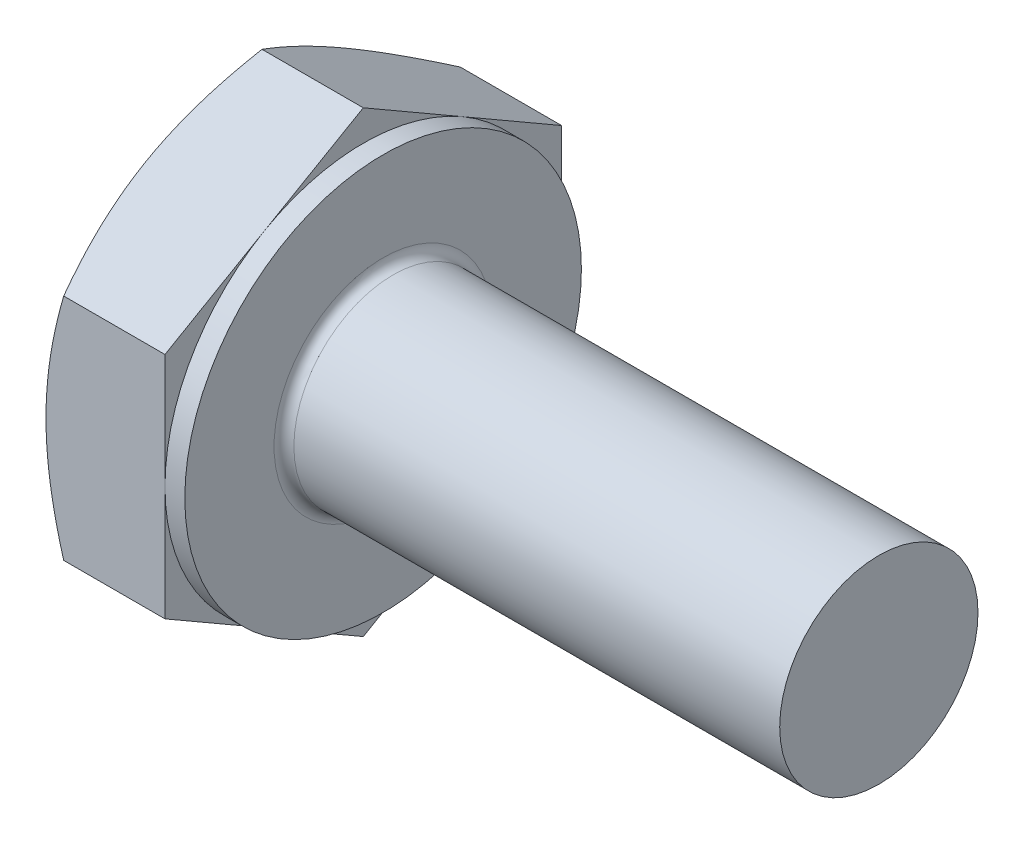
SolidWorks part; units mm, degrees
extrude "基体-拉伸" add sketch "草图1" along normal blind 1.4
sketch "草图1" plane through (0, 0, 0) normal (1, 0, 0) x (0, 0, -1)
  line L0 (2, 1.1547) -> (2, -1.1547)
  line L1 (-2, 1.1547) -> (-2, -1.1547)
  line L2 (2, -1.1547) -> (0, -2.3094)
  line L3 (0, -2.3094) -> (-2, -1.1547)
  line L4 (2, 1.1547) -> (0, 2.3094)
  line L5 (0, 2.3094) -> (-2, 1.1547)
  dimension "s" = 4
  dimension "D2" = 120
  dimension "D3" = 2
  dimension "D4" = 2
  dimension "D5" = 2
revolve "切除-旋转1" cut sketch "草图3" angle 360 about L6
sketch "草图3" plane through (0, 0, 0) normal (0, 0, 1) x (1, 0, 0)
  line L0 (0, 2) -> (3.0654, 7.3094)
  line L1 (0, 2.3094) -> (0, 1.1547) construction
  line L2 (3.0654, 7.3094) -> (3.0654, 12.3094)
  line L3 (3.0654, 12.3094) -> (-10, 12.3094)
  line L4 (-10, 12.3094) -> (-10, 2)
  line L5 (-10, 2) -> (0, 2)
  line L6 (0, 0) -> (99.06, 0) construction
  line L7 (1.4, 2.3094) -> (0, 2.3094) construction
  dimension "D1" = 2
  dimension "D2" = 5
  dimension "D3" = 10
  dimension "D4" = 5
  dimension "Head_ch_ang" = 30
material "5.6级"
ref_plane "前视" through (0, 0, 0) normal (0, 0, 1) x (1, 0, 0)
ref_plane "上视" through (0, 0, 0) normal (0, 1, 0) x (1, 0, 0)
ref_plane "右视" through (0, 0, 0) normal (1, 0, 0) x (0, 0, -1)
sketch "草图2" plane through (0, 0, 0) normal (0, 0, 1) x (1, 0, 0)
  line L0 (0, 1.1547) -> (0, -1.1547) construction
  line L1 (0, 0) -> (21.4, 0)
  line L2 (0, 0) -> (0, 1)
  line L3 (0, 1) -> (7.7917, 1)
  line L4 (21.4, 0) -> (21.4, 0.6536)
  line L5 (1.4, 2.3094) -> (1.4, 1.1547) construction
  line L7 (0, 0) -> (96.52, 0) construction
  line L8 (21.4, -0.6536) -> (7.7917, -1) construction
  line L9 (0, -1) -> (7.7917, -1) construction
  line L10 (1.8, 15.24) -> (1.8, -1.27) construction
  line L11 (11.4, 15.24) -> (11.4, -1.27) construction
  line L12 (1.4, 1.1547) -> (1.4, -1.1547) construction
  line L13 (7.7917, 1) -> (21.4, 1)
  line L14 (21.4, 1) -> (21.4, 0.6536)
revolve "凸台-旋转1" add sketch "草图2" angle 360 about L7
cosmetic thread "螺旋线1" parameters "Thread_length"=10, "Thread_minor"=1.3072
sketch "草图5" plane through (0, 0, 0) normal (0, 0, 1) x (1, 0, 0)
  line L0 (1.4, 2) -> (-1.6654, 7.3094)
  line L1 (1.4, 2.3094) -> (1.4, 1.1547) construction
  line L2 (-1.6654, 7.3094) -> (-1.6654, 12.3094)
  line L3 (-1.6654, 12.3094) -> (8.3346, 12.3094)
  line L4 (8.3346, 12.3094) -> (8.3346, 2)
  line L5 (8.3346, 2) -> (1.4, 2)
  line L7 (1.4, 2.3094) -> (0.1786, 2.3094) construction
  line L8 (0, 0) -> (99.06, 0) construction
  line L9 (0, 0) -> (99.06, 0) construction
  dimension "D1" = 2
  dimension "D2" = 5
  dimension "D3" = 10
  dimension "D4" = 5
  dimension "Head_ch_ang" = 30
revolve "切除-旋转2" cut sketch "草图5" angle 360 about L8
sketch "草图4" plane through (0, 0, 0) normal (0, 0, 1) x (1, 0, 0)
  line L1 (1.4, 2.3094) -> (1.4, 1.1547) construction
  line L2 (1.4, 2) -> (1.2, 2)
  line L3 (1.4, 2) -> (1.4, 12.3094)
  line L4 (1.4, 12.3094) -> (1.2, 12.3094)
  line L5 (0, 0) -> (95.25, 0) construction
  line L6 (0, 0) -> (96.52, 0) construction
  line L7 (1.2, 2) -> (1.2, 12.3094)
  line L8 (1.2214, 2.3094) -> (0.1786, 2.3094) construction
  dimension "D2" = 10
  dimension "D1" = 4
revolve "切除-旋转3" cut sketch "草图4" angle 360 about L5
chamfer "倒角" distance 0.32 angle 45 1 edges at (21.4, 0, 1)
fillet "圆角" radius 0.1 1 edges at (1.4, 0, -1)
sketch "草图6" plane through (0, 0, 0) normal (0, 0, 1) x (1, 0, 0)
  line L0 (11.4, -0.6536) -> (11.2, -1)
  line L1 (11.4, -0.6536) -> (11.6, -1)
  line L2 (11.6, -1) -> (11.6, -1.25)
  line L3 (-3.175, 0) -> (5.1513, 0) construction
  line L5 (11.6, -1.25) -> (11.2, -1.25)
  line L6 (11.2, -1.25) -> (11.2, -1)
  dimension "Thread_minor" = 1.3072
  dimension "Diameter" = 2
  dimension "Start" = 11.4
revolve "切除-旋转4" [suppressed] cut sketch "草图6" angle 360 about L3
pattern_linear "阵列(线性)1" [suppressed]
sketch "草图7" plane through (21.4, 0, 0) normal (1, 0, 0) x (0, 0, -1)
  circle A0 centre (0, 0) radius 1.5929
extrude "切除-拉伸1" cut sketch "草图7" against normal blind 15
equation "\"D3@草图1\" = \"s@草图1\" / 2"
equation "\"D4@草图1\" = \"D3@草图1\""
equation "\"D5@草图1\" = \"D4@草图1\""
equation "\"Thread_minor@螺旋线1\" = \"Minor_dia@草图2\""
equation "\"D1@草图3\" = \"s@草图1\" / 2"
equation "\"D1@草图5\" = \"s@草图1\" / 2"
equation "\"Head_ch_ang@草图5\" = \"Head_ch_ang@草图3\""
equation "\"D1@草图4\" = \"s@草图1\""
equation "\"Thread_length@螺旋线1\" = ((sgn( (\"l@草图2\" - \"p@草图2\" ) - \"h@草图2\" )-1)*( (\"l@草图2\" - \"p@草图2\" ) - \"h@草图2\" ))/-2+ \"h@草图2\""
equation "\"Thread_minor@草图6\" = \"Minor_dia@草图2\""
equation "\"Diameter@草图6\" = \"m@草图2\""
equation "\"Overcut@草图6\" = \"m@草图2\" * 1.25"
equation "\"Start@草图6\" = \"k@基体-拉伸\" + \"l@草图2\" - \"Thread_length@螺旋线1\"  '---Non-countersunk---"
equation "\"Num_threads@阵列(线性)1\" = int( \"Thread_length@螺旋线1\" / \"p@草图2\" + 0.999 )  + 1"
equation "\"Advance@阵列(线性)1\" = \"Thread_length@螺旋线1\" /  (\"Num_threads@阵列(线性)1\" - 1) 'relax it"
equation "\"Num_threads@阵列(线性)1\" = \"Num_threads@阵列(线性)1\" - sgn( \"Num_threads@阵列(线性)1\" - 1) '---chamfered tips only---"
equation "\"Minor_dia@草图2\" = \"m@草图2\"-\"p@草图2\" * 1.732"
equation "\"D1@倒角\" = \"p@草图2\"*0.8"
